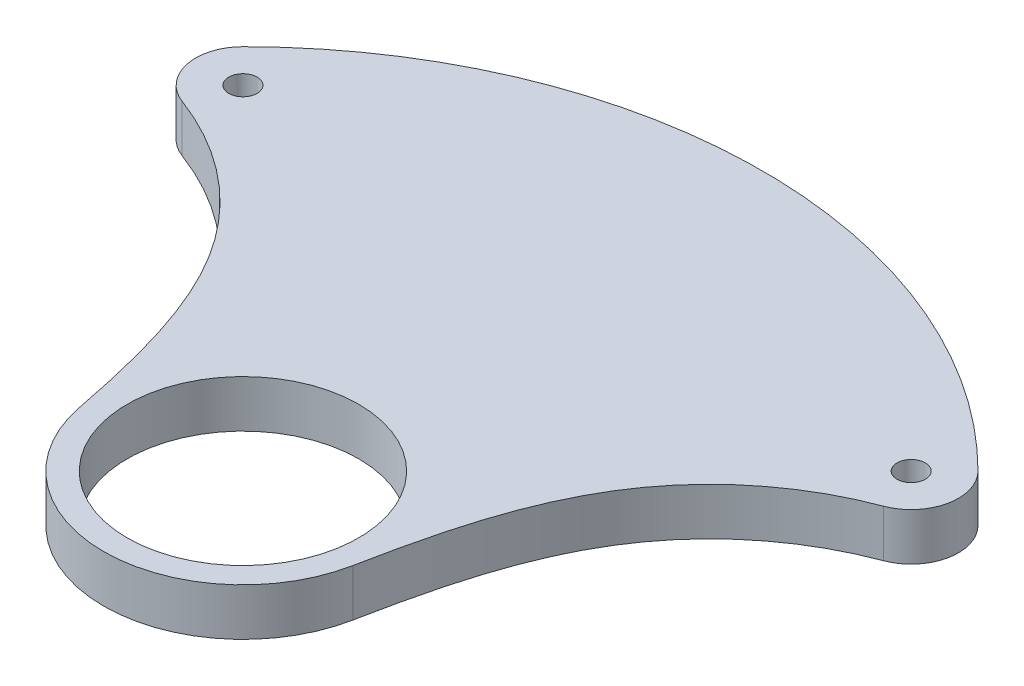
SolidWorks part; units mm, degrees
ref_plane "Front Plane" through (0, 0, 0) normal (0, 0, 1) x (1, 0, 0)
ref_plane "Top Plane" through (0, 0, 0) normal (0, 1, 0) x (1, 0, 0)
ref_plane "Right Plane" through (0, 0, 0) normal (1, 0, 0) x (0, 0, -1)
sketch "Sketch2" plane through (0, 0, 0) normal (0, 1, 0) x (1, 0, 0)
  line L0 (-31.8198, 31.8198) -> (-38.8909, 38.8909)
  line L1 (0, -55) -> (0, 55) construction
  line L2 (14.75, 0) -> (45, 0) construction
  circle A0 centre (0, 0) radius 45 construction
  circle A1 centre (0, 0) radius 55
  arc A2 (-38.8909, 38.8909) -> (-31.8198, 31.8198) centre (-35.3553, 35.3553) ccw
  arc A3 (38.8909, 38.8909) -> (31.8198, 31.8198) centre (35.3553, 35.3553) cw
  circle A4 centre (0, 0) radius 12.25
  circle A5 centre (0, 0) radius 14.75
  circle A6 centre (0, 0) radius 29.875 construction
  spline S0 degree 3 poles (-37.1013, 30.6701) (-31.0879, 28.4292) (-19.5444, 19.3017) (-16.0486, 5.1692) (-14.473, -2.8453) knots 0 0 0 0 0.434164 1 1 1 1
  spline S1 degree 3 poles (37.1013, 30.6701) (31.0879, 28.4292) (19.5444, 19.3017) (16.0486, 5.1692) (14.473, -2.8453) knots 0 0 0 0 0.434164 1 1 1 1
  point P23 (29.875, 0)
  point P24 (18.8981, 9.7172)
  point P25 (18.0987, 11.1354)
  point P26 (19.5932, 10.805)
  point P27 (20.6917, 17.9233)
  dimension "D2" = 110
  dimension "D4" = 24.5
  dimension "D1" = 10
  dimension "D3" = 45
  dimension "D5" = 2.5
extrude "Boss-Extrude1" add sketch "Sketch2" along normal blind 5
sketch "Sketch3" plane through (0, 5, 0) normal (0, 1, 0) x (1, 0, 0)
  line L0 (0, 0) -> (-35.3553, 35.3553) construction
  line L1 (-35.3553, 35.3553) -> (35.3553, 35.3553) construction
  line L2 (35.3553, 35.3553) -> (0, 0) construction
  line L3 (0, -55) -> (0, 55) construction
  circle A0 centre (-35.3553, 35.3553) radius 1.5
  circle A1 centre (35.3553, 35.3553) radius 1.5
  dimension "D1" = 3
extrude "Cut-Extrude1" cut sketch "Sketch3" against normal up to next
equation "\"Width\"= 10mm"
equation "\"Thick\"= 5mm"
equation "\"Diameter\" = 110"
equation "\"D2@Sketch2\"= \"Diameter\""
equation "\"DegreeOfArc\" = 90deg"
equation "\"D3@Sketch2\"= \"DegreeOfArc\" / 2"
equation "\"D1@Boss-Extrude1\"= \"Thick\""
equation "\"D1@Sketch2\"= \"Width\""
equation "\"D4@Sketch2\"=24.5"
